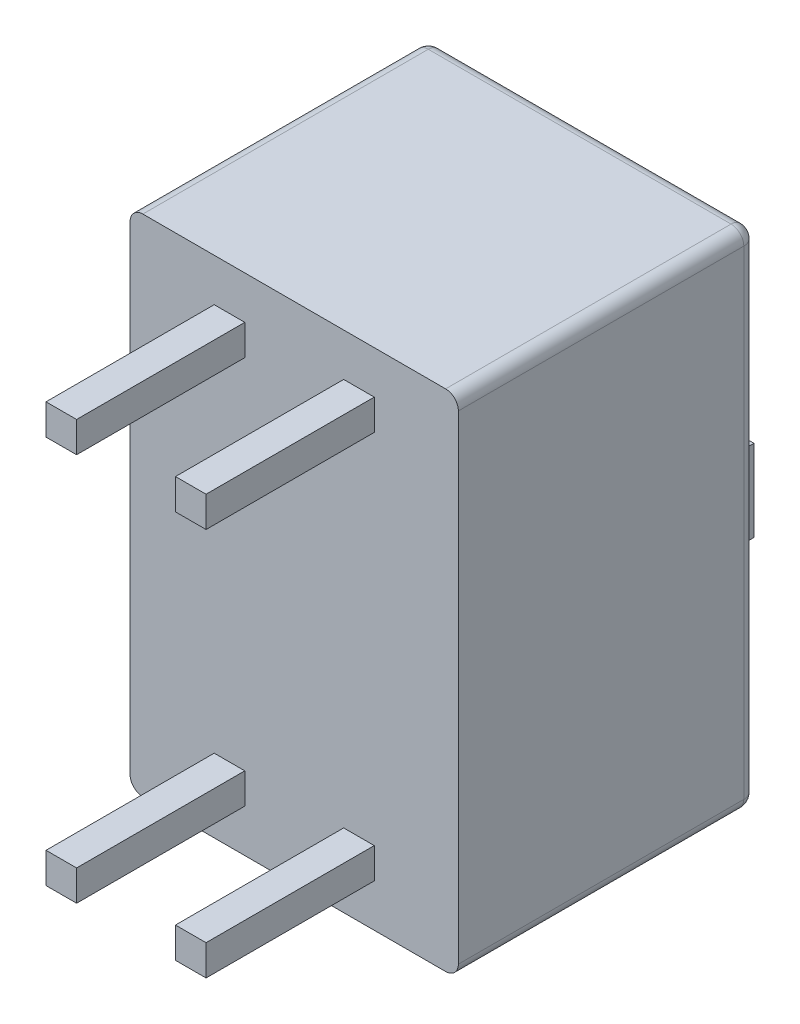
SolidWorks part; units mm, degrees
ref_plane "Ön Düzlem" through (0, 0, 0) normal (0, 0, 1) x (1, 0, 0)
ref_plane "Üst Düzlem" through (0, 0, 0) normal (0, 1, 0) x (1, 0, 0)
ref_plane "Sağ Düzlem" through (0, 0, 0) normal (1, 0, 0) x (0, 0, -1)
sketch "Çizim1" plane through (0, 0, 0) normal (0, 0, 1) x (1, 0, 0)
  line L1 (-3.22, 4.95) -> (3.22, 4.95)
  line L2 (-3.22, 4.95) -> (-3.22, -4.95)
  line L3 (-3.22, -4.95) -> (3.22, -4.95)
  line L4 (3.22, 4.95) -> (3.22, -4.95)
  line L5 (-3.22, 4.95) -> (3.22, -4.95) construction
  line L6 (-3.22, -4.95) -> (3.22, 4.95) construction
  point P0 (0, 0)
extrude "Yükseklik-Ekstrüzyon1" add sketch "Çizim1" along normal blind 5.85
sketch "Çizim2" plane through (0, 0, 0) normal (0, 0, -1) x (-1, 0, 0)
  line L5 (-1.97, -1.6) -> (-0.57, -1.6)
  line L6 (-1.97, -1.6) -> (-1.97, 1.6)
  line L7 (-1.97, 1.6) -> (-0.57, 1.6)
  line L8 (-0.57, -1.6) -> (-0.57, 1.6)
  line L9 (-1.97, -1.6) -> (-0.57, 1.6) construction
  line L10 (-1.97, 1.6) -> (-0.57, -1.6) construction
  line L11 (0.57, -1.6) -> (1.97, -1.6)
  line L12 (0.57, -1.6) -> (0.57, 1.6)
  line L13 (0.57, 1.6) -> (1.97, 1.6)
  line L14 (1.97, -1.6) -> (1.97, 1.6)
  line L15 (0.57, -1.6) -> (1.97, 1.6) construction
  line L16 (0.57, 1.6) -> (1.97, -1.6) construction
extrude "Kes-Ekstrüzyon1" cut sketch "Çizim2" against normal blind 1
sketch "Çizim4" plane through (0, 0, 1) normal (0, 0, -1) x (-1, 0, 0)
  line L0 (-0.57, -1.6) -> (-0.57, 1.6) construction
  line L1 (-1.97, -1.6) -> (-0.57, -1.6)
  line L2 (-1.97, -1.6) -> (-1.97, 0)
  line L3 (-1.97, 0) -> (-0.57, 0)
  line L4 (-0.57, -1.6) -> (-0.57, 0)
  line L5 (1.97, -1.6) -> (1.97, 1.6) construction
  line L6 (0.57, -1.6) -> (1.97, -1.6)
  line L7 (0.57, -1.6) -> (0.57, 0)
  line L8 (0.57, 0) -> (1.97, 0)
  line L9 (1.97, -1.6) -> (1.97, 0)
extrude "Yükseklik-Ekstrüzyon3" add sketch "Çizim4" along normal blind 2.2
sketch "Çizim5" plane through (0, 0, 1) normal (0, 0, -1) x (-1, 0, 0)
  line L1 (-1.97, 0) -> (-0.57, 0)
  line L2 (-1.97, 0) -> (-1.97, 1.6)
  line L3 (-1.97, 1.6) -> (-0.57, 1.6)
  line L4 (-0.57, 0) -> (-0.57, 1.6)
  line L5 (0.57, 0) -> (1.97, 0)
  line L6 (0.57, 0) -> (0.57, 1.6)
  line L7 (0.57, 1.6) -> (1.97, 1.6)
  line L8 (1.97, 0) -> (1.97, 1.6)
extrude "Yükseklik-Ekstrüzyon4" add sketch "Çizim5" along normal blind 0.9 separate body
fillet "Radyus1" radius 0.25 8 edges at (3.22, -4.95, 2.925) (3.22, 0, 0) (3.22, 4.95, 2.925) (0, 4.95, 0) (-3.22, 4.95, 2.925) (0, -4.95, 0) (-3.22, 0, 0) (-3.22, -4.95, 2.925)
sketch "Çizim6" plane through (0, 0, 5.85) normal (0, 0, 1) x (1, 0, 0)
  line L7 (0.97, -4.11) -> (1.57, -4.11)
  line L8 (0.97, -4.11) -> (0.97, -3.51)
  line L9 (0.97, -3.51) -> (1.57, -3.51)
  line L10 (1.57, -4.11) -> (1.57, -3.51)
  line L11 (0.97, -4.11) -> (1.57, -3.51) construction
  line L12 (0.97, -3.51) -> (1.57, -4.11) construction
  line L13 (-1.57, -4.11) -> (-0.97, -4.11)
  line L14 (-1.57, -4.11) -> (-1.57, -3.51)
  line L15 (-1.57, -3.51) -> (-0.97, -3.51)
  line L16 (-0.97, -4.11) -> (-0.97, -3.51)
  line L17 (-1.57, -4.11) -> (-0.97, -3.51) construction
  line L18 (-1.57, -3.51) -> (-0.97, -4.11) construction
  line L19 (-1.57, 3.51) -> (-0.97, 3.51)
  line L20 (-1.57, 3.51) -> (-1.57, 4.11)
  line L21 (-1.57, 4.11) -> (-0.97, 4.11)
  line L22 (-0.97, 3.51) -> (-0.97, 4.11)
  line L23 (-1.57, 3.51) -> (-0.97, 4.11) construction
  line L24 (-1.57, 4.11) -> (-0.97, 3.51) construction
  line L25 (0.97, 3.51) -> (1.57, 3.51)
  line L26 (0.97, 3.51) -> (0.97, 4.11)
  line L27 (0.97, 4.11) -> (1.57, 4.11)
  line L28 (1.57, 3.51) -> (1.57, 4.11)
  line L29 (0.97, 3.51) -> (1.57, 4.11) construction
  line L30 (0.97, 4.11) -> (1.57, 3.51) construction
extrude "Yükseklik-Ekstrüzyon5" add sketch "Çizim6" along normal blind 3.3
